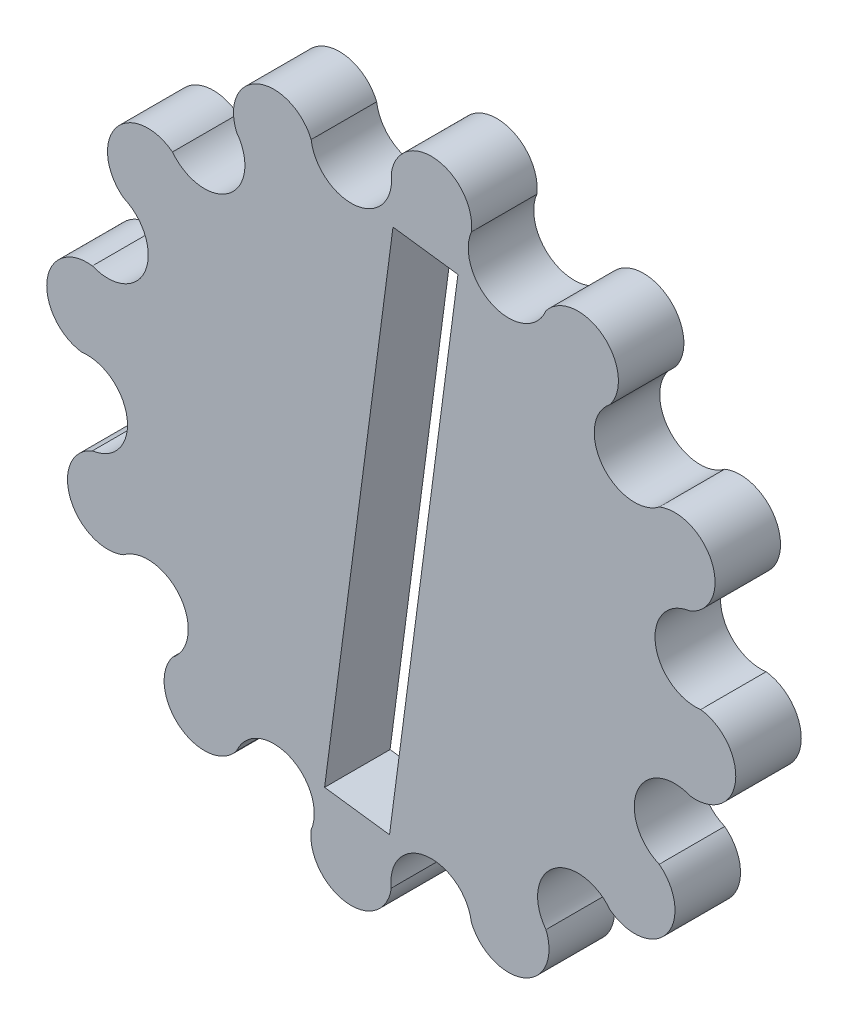
SolidWorks part; units mm, degrees
ref_plane "Front Plane" through (0, 0, 0) normal (0, 0, 1) x (1, 0, 0)
ref_plane "Top Plane" through (0, 0, 0) normal (0, 1, 0) x (1, 0, 0)
ref_plane "Right Plane" through (0, 0, 0) normal (1, 0, 0) x (0, 0, -1)
sketch "Sketch1" plane through (0, 0, 0) normal (0, 0, 1) x (1, 0, 0)
  line L1 (3.75, 13.9952) -> (3.8823, 14.4889)
  arc A1 (0, 15) -> (3.8823, 14.4889) centre (1.9411, 14.7444) cw
  arc A2 (7.5, 12.9904) -> (10.6066, 10.6066) centre (9.0533, 11.7985) cw
  arc A3 (12.9904, 7.5) -> (14.4889, 3.8823) centre (13.7396, 5.6911) cw
  arc A4 (15, 0) -> (14.4889, -3.8823) centre (14.7444, -1.9411) cw
  arc A5 (12.9904, -7.5) -> (10.6066, -10.6066) centre (11.7985, -9.0533) cw
  arc A6 (7.5, -12.9904) -> (3.8823, -14.4889) centre (5.6911, -13.7396) cw
  arc A7 (0, -15) -> (-3.8823, -14.4889) centre (-1.9411, -14.7444) cw
  arc A8 (-7.5, -12.9904) -> (-10.6066, -10.6066) centre (-9.0533, -11.7985) cw
  arc A9 (-12.9904, -7.5) -> (-14.4889, -3.8823) centre (-13.7396, -5.6911) cw
  arc A10 (-15, 0) -> (-14.4889, 3.8823) centre (-14.7444, 1.9411) cw
  arc A11 (-12.9904, 7.5) -> (-10.6066, 10.6066) centre (-11.7985, 9.0533) cw
  arc A12 (-7.5, 12.9904) -> (-3.8823, 14.4889) centre (-5.6911, 13.7396) cw
  arc A13 (3.8823, 14.4889) -> (7.5, 12.9904) centre (5.6911, 13.7396) ccw
  arc A14 (10.6066, 10.6066) -> (12.9904, 7.5) centre (11.7985, 9.0533) ccw
  arc A15 (14.4889, 3.8823) -> (15, 0) centre (14.7444, 1.9411) ccw
  arc A16 (14.4889, -3.8823) -> (12.9904, -7.5) centre (13.7396, -5.6911) ccw
  arc A17 (10.6066, -10.6066) -> (7.5, -12.9904) centre (9.0533, -11.7985) ccw
  arc A18 (3.8823, -14.4889) -> (0, -15) centre (1.9411, -14.7444) ccw
  arc A19 (-3.8823, -14.4889) -> (-7.5, -12.9904) centre (-5.6911, -13.7396) ccw
  arc A20 (-10.6066, -10.6066) -> (-12.9904, -7.5) centre (-11.7985, -9.0533) ccw
  arc A21 (-14.4889, -3.8823) -> (-15, 0) centre (-14.7444, -1.9411) ccw
  arc A22 (-14.4889, 3.8823) -> (-12.9904, 7.5) centre (-13.7396, 5.6911) ccw
  arc A23 (-10.6066, 10.6066) -> (-7.5, 12.9904) centre (-9.0533, 11.7985) ccw
  arc A24 (-3.8823, 14.4889) -> (0, 15) centre (-1.9411, 14.7444) ccw
  dimension "D3" = 12
  dimension "D4" = 12
extrude "Boss-Extrude1" add sketch "Sketch1" along normal blind 3.175 contours A24 A12 A23 A11 A22 A10 A21 A9 A20 A8 A19 A7 A18 A6 A17 A5 A16 A4 A15 A3 A14 A2 A13 A1
sketch "Sketch3" plane through (0, 0, 0) normal (0, 0, 1) x (1, 0, 0)
  line L4 (3.2316, 12.3841) -> (0.0838, 12.7986)
  line L6 (-0.0838, -12.7986) -> (-3.2316, -12.3841)
  line L7 (-3.2316, -12.3841) -> (0.0838, 12.7986)
  line L8 (-0.0838, -12.7986) -> (3.2316, 12.3841)
  point P14 (0, 0)
extrude "Cut-Extrude1" cut sketch "Sketch3" along normal blind 3.175 contours L8 L4 L7 L6
